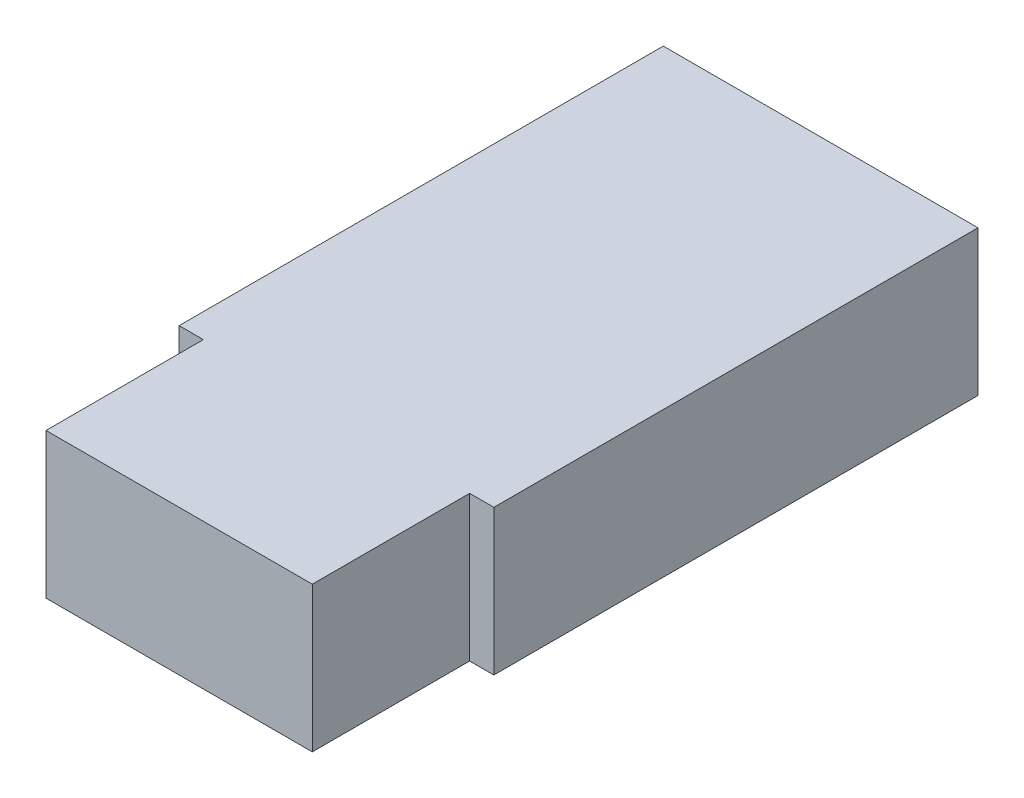
SolidWorks part; units mm, degrees
ref_plane "Front Plane" through (0, 0, 0) normal (0, 0, 1) x (1, 0, 0)
ref_plane "Top Plane" through (0, 0, 0) normal (0, 1, 0) x (1, 0, 0)
ref_plane "Right Plane" through (0, 0, 0) normal (1, 0, 0) x (0, 0, -1)
sketch "Sketch1" plane through (0, 0, 0) normal (0, 1, 0) x (1, 0, 0)
  line L0 (11, -20) -> (13, -20)
  line L1 (-13, 20) -> (13, 20)
  line L2 (-13, 20) -> (-13, -20)
  line L3 (-13, -20) -> (-11, -20)
  line L4 (13, 20) -> (13, -20)
  line L5 (-13, 20) -> (13, -20) construction
  line L6 (-13, -20) -> (13, 20) construction
  line L8 (11, -20) -> (11, -33)
  line L9 (11, -33) -> (-11, -33)
  line L10 (-11, -20) -> (-11, -33)
  point P0 (0, 0)
  dimension "D1" = 26
  dimension "D2" = 40
  dimension "D3" = 13
  dimension "D4" = 2
  dimension "D5" = 2
extrude "Boss-Extrude1" add sketch "Sketch1" along normal blind 12
